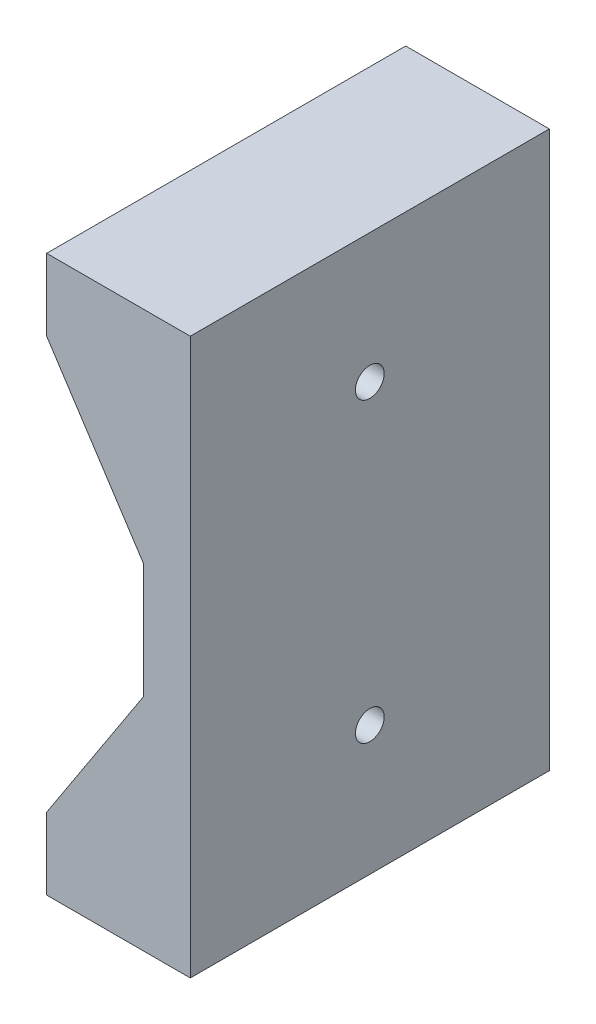
SolidWorks part; units mm, degrees
ref_plane "Front Plane" through (0, 0, 0) normal (0, 0, 1) x (1, 0, 0)
ref_plane "Top Plane" through (0, 0, 0) normal (0, 1, 0) x (1, 0, 0)
ref_plane "Right Plane" through (0, 0, 0) normal (1, 0, 0) x (0, 0, -1)
sketch "Sketch1" plane through (15, 0, 0) normal (1, 0, 0) x (0, 0, -1)
  line L0 (-55.1107, 20.7) -> (-55.1107, 38.7) construction
  line L1 (-80.1107, 38.7) -> (-30.1107, 38.7)
  line L2 (-80.1107, 38.7) -> (-80.1107, -38.7)
  line L3 (-80.1107, -38.7) -> (-30.1107, -38.7)
  line L4 (-30.1107, 38.7) -> (-30.1107, -38.7)
  line L5 (0, 0) -> (-80.1107, 0) construction
  circle A0 centre (-55.1107, 20.7) radius 2
  circle A1 centre (-55.1107, -20.7) radius 2
  point P10 (-30.1107, 0)
  dimension "D3" = 4
  dimension "D1" = 18
  dimension "D2" = 50
extrude "Boss-Extrude1" add sketch "Sketch1" against normal blind 3
sketch "Sketch2" plane through (12, 0, 0) normal (-1, 0, 0) x (0, 0, 1)
  line L0 (80.1107, 38.7) -> (80.1107, -38.7) construction
  line L1 (30.1107, 38.7) -> (80.1107, 38.7)
  line L2 (30.1107, 38.7) -> (30.1107, 28.7)
  line L3 (30.1107, 28.7) -> (42.4221, 28.7)
  line L4 (80.1107, 38.7) -> (80.1107, 28.7)
  line L5 (67.7993, 28.7) -> (80.1107, 28.7)
  line L6 (30.1107, 33.7) -> (80.1107, 33.7) construction
  arc A0 (42.4221, 28.7) -> (67.7993, 28.7) centre (55.1107, 20.7) cw
  circle A1 centre (34.1107, 33.7) radius 1.75
  circle A2 centre (41.1107, 33.7) radius 1.75
  circle A3 centre (69.1107, 33.7) radius 1.75
  circle A4 centre (76.1107, 33.7) radius 1.75
  dimension "D2" = 15
  dimension "D3" = 3.5
  dimension "D1" = 10
  dimension "D4" = 4
  dimension "D5" = 7
  dimension "D7" = 4
  dimension "D8" = 7
extrude "Boss-Extrude2" add sketch "Sketch2" along normal blind 17
mirror "Mirror1" about plane through (0, 0, 0) normal (0, 1, 0) of "Boss-Extrude2"
sketch "Sketch3" plane through (12, 0, 0) normal (-1, 0, 0) x (0, 0, 1)
  line L0 (80.1107, 28.7) -> (80.1107, -28.7) construction
  line L1 (80.1107, 8) -> (30.1107, 8)
  line L2 (80.1107, 8) -> (80.1107, -8)
  line L3 (80.1107, -8) -> (30.1107, -8)
  line L4 (30.1107, 8) -> (30.1107, -8)
  line L5 (200, 8) -> (0, 8) construction
  line L6 (30.1107, -28.7) -> (30.1107, 28.7) construction
  line L7 (200, -8) -> (0, -8) construction
extrude "Boss-Extrude3" add sketch "Sketch3" along normal blind 3.5
fillet "Fillet1" [suppressed] radius 10
chamfer "Chamfer1" [suppressed] distance 15 angle 60
sketch "Sketch4" [suppressed] plane through (8.5, 0, 0) normal (-1, 0, 0) x (0, 0, 1)
  line L0 (80.1107, 8) -> (30.1107, 8) construction
  line L1 (36.1107, 8) -> (74.1107, 8)
  line L2 (36.1107, 8) -> (36.1107, -8)
  line L3 (36.1107, -8) -> (74.1107, -8)
  line L4 (74.1107, 8) -> (74.1107, -8)
  line L5 (30.1107, -8) -> (80.1107, -8) construction
  line L6 (30.1107, 8) -> (30.1107, -8) construction
  line L7 (80.1107, -8) -> (80.1107, 8) construction
  dimension "D1" = 6
  dimension "D2" = 6
extrude "Cut-Extrude1" [suppressed] cut sketch "Sketch4" against normal up to surface (3.5 mm away)
sketch "Sketch5" [suppressed] plane through (8.5, 0, 0) normal (-1, 0, 0) x (0, 0, 1)
  line L0 (47.1289, 8) -> (30.1107, 8) construction
  line L1 (38.1107, 8) -> (72.1107, 8)
  line L2 (38.1107, 8) -> (38.1107, -8)
  line L3 (38.1107, -8) -> (72.1107, -8)
  line L4 (72.1107, 8) -> (72.1107, -8)
  line L5 (30.1107, -8) -> (80.1107, -8) construction
  line L6 (30.1107, 8) -> (30.1107, -8) construction
  line L7 (80.1107, -8) -> (80.1107, 8) construction
  dimension "D1" = 8
  dimension "D2" = 8
extrude "Cut-Extrude2" [suppressed] cut sketch "Sketch5" against normal up to surface (3.5 mm away)
fillet "Fillet2" [suppressed] radius 14
fillet "Fillet4" [suppressed] radius 21
sketch "Sketch6" plane through (8.5, 0, 0) normal (-1, 0, 0) x (0, 0, 1)
  line L0 (80.1107, 8) -> (30.1107, 8) construction
  line L1 (40.1107, 8) -> (70.1107, 8)
  line L2 (40.1107, 8) -> (40.1107, -8)
  line L3 (40.1107, -8) -> (70.1107, -8)
  line L4 (70.1107, 8) -> (70.1107, -8)
  line L5 (30.1107, -8) -> (80.1107, -8) construction
  line L6 (30.1107, 8) -> (30.1107, -8) construction
  line L7 (80.1107, -8) -> (80.1107, 8) construction
  dimension "D1" = 10
  dimension "D2" = 10
extrude "Cut-Extrude3" cut sketch "Sketch6" against normal up to surface (3.5 mm away) up to face at (12, 20.7, 53.1107)
loft "Loft2" add section face at (3.5, 28.7, 36.2664) section face at (10.25, 8, 35.1107)
loft "Loft3" add section face at (10.25, 8, 75.1107) section face at (3.5, 28.7, 73.955)
loft "Loft4" add section face at (10.25, -8, 35.1107) section face at (3.5, -28.7, 36.2664)
loft "Loft5" add section face at (3.5, -28.7, 73.955) section face at (10.25, -8, 75.1107)
equation "\"2o\"=30"
